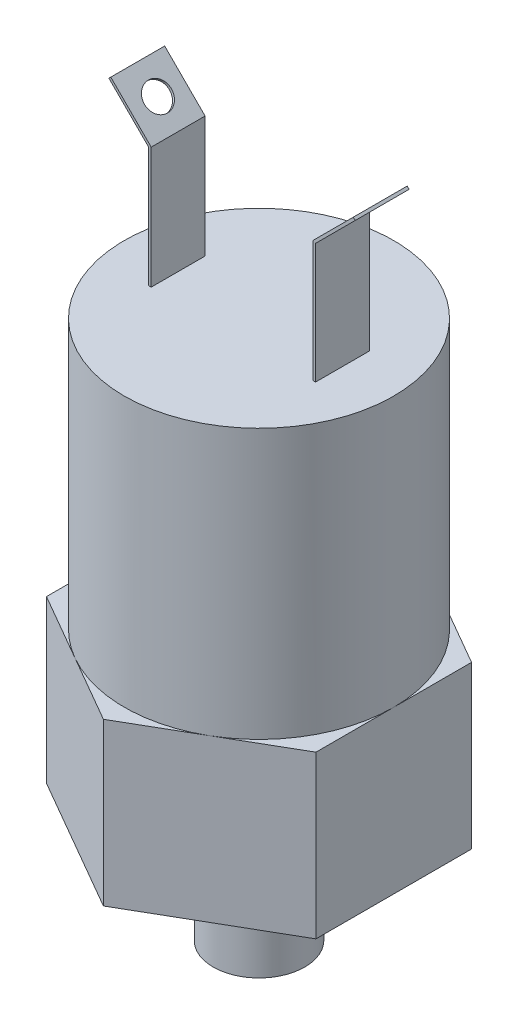
SolidWorks part; units mm, degrees
ref_plane "Front Plane" through (0, 0, 0) normal (0, 0, 1) x (1, 0, 0)
ref_plane "Top Plane" through (0, 0, 0) normal (0, 1, 0) x (1, 0, 0)
ref_plane "Right Plane" through (0, 0, 0) normal (1, 0, 0) x (0, 0, -1)
sketch "Sketch1" plane through (0, 0, 0) normal (0, 1, 0) x (1, 0, 0)
  circle A0 centre (0, 0) radius 4.318
  dimension "D1" = 8.636
extrude "Boss-Extrude1" add sketch "Sketch1" along normal blind 10.16
cosmetic thread "Cosmetic Thread1" parameters "D2"=7.636
sketch "Sketch2" plane through (0, 10.16, 0) normal (0, 1, 0) x (1, 0, 0)
  line L1 (0, 14.6647) -> (-12.7, 7.3323)
  line L2 (-12.7, 7.3323) -> (-12.7, -7.3323)
  line L3 (-12.7, -7.3323) -> (0, -14.6647)
  line L4 (0, -14.6647) -> (12.7, -7.3323)
  line L5 (12.7, -7.3323) -> (12.7, 7.3323)
  line L6 (12.7, 7.3323) -> (0, 14.6647)
  circle A0 centre (0, 0) radius 12.7 construction
  point P1 (0, 0)
  dimension "D1" = 25.4
extrude "Boss-Extrude2" add sketch "Sketch2" along normal blind 15.24
sketch "Sketch3" plane through (0, 25.4, 0) normal (0, 1, 0) x (1, 0, 0)
  circle A0 centre (0, 0) radius 12.7
  dimension "D1" = 25.4
extrude "Boss-Extrude3" add sketch "Sketch3" along normal blind 25.4
sketch "Sketch4" plane through (0, 0, 0) normal (0, 0, 1) x (1, 0, 0)
  line L0 (7.62, 50.8) -> (7.62, 62.23)
  line L1 (12.7, 50.8) -> (-12.7, 50.8) construction
  line L2 (7.62, 62.23) -> (11.43, 66.04)
  line L3 (12.7, 25.4) -> (12.7, 50.8) construction
  point P4 (10.5211, 66.04)
  dimension "D1" = 15.24
  dimension "D2" = 45
  dimension "D3" = 11.43
  dimension "D4" = 5.08
extrude "Extrude-Thin1" add sketch "Sketch4" along normal mid plane 5.08 thin
sketch "Sketch5" plane through (-27.305, 27.305, 0) normal (-0.7071, 0.7071, 0) x (0, 0, 1)
  line L0 (-2.54, 54.7796) -> (2.54, 49.3914) construction
  line L1 (2.54, 54.7796) -> (-2.54, 49.3914) construction
  circle A0 centre (0, 52.0855) radius 1.27
  dimension "D1" = 2.54
extrude "Cut-Extrude1" cut sketch "Sketch5" against normal up to next
mirror "Mirror1" about plane through (0, 0, 0) normal (1, 0, 0) of "Cut-Extrude1", "Extrude-Thin1"
